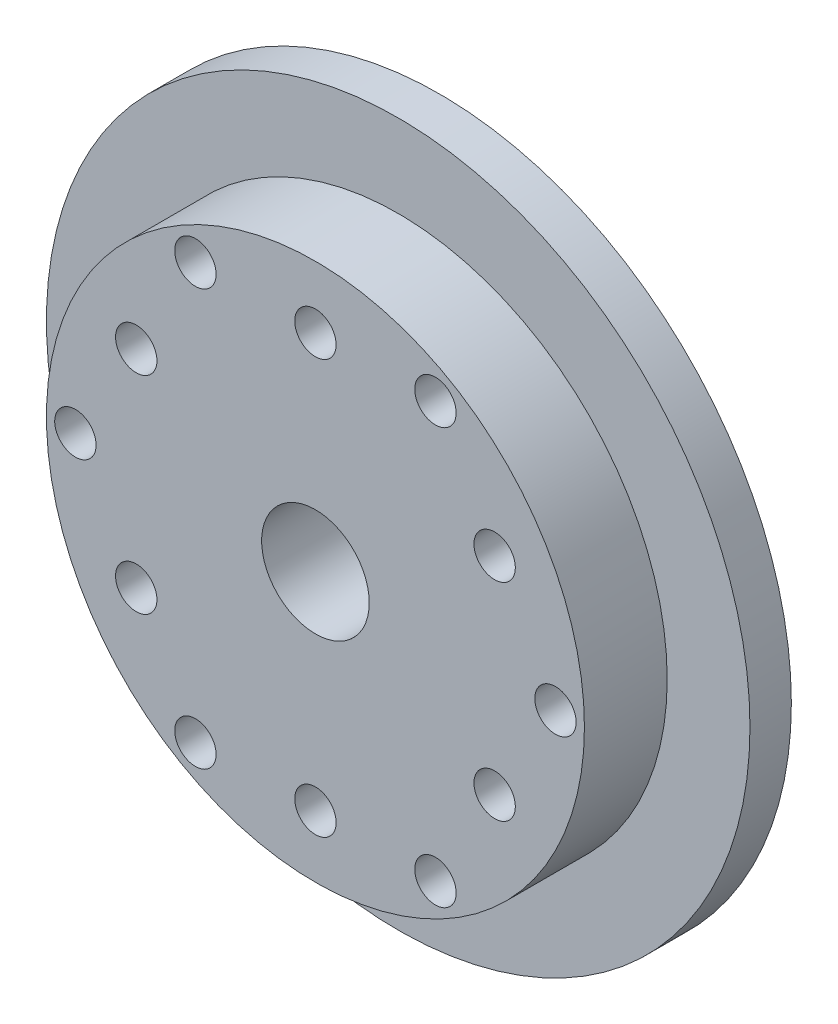
SolidWorks part; units mm, degrees
other "Markup1"
sketch "Sketch6"
ref_plane "Front Plane" through (0, 0, 0) normal (0, 0, 1) x (1, 0, 0)
ref_plane "Top Plane" through (0, 0, 0) normal (0, 1, 0) x (1, 0, 0)
ref_plane "Right Plane" through (0, 0, 0) normal (1, 0, 0) x (0, 0, -1)
sketch "Sketch1" plane through (0, 0, 0) normal (0, 0, 1) x (1, 0, 0)
  circle A0 centre (0, 0) radius 12
  circle A1 centre (0, 0) radius 42.5
  dimension "D1" = 24
  dimension "D2" = 85
extrude "Boss-Extrude1" add sketch "Sketch1" along normal blind 5
sketch "Sketch2" plane through (0, 0, 5) normal (0, 0, 1) x (1, 0, 0)
  circle A0 centre (0, 0) radius 32.5
  circle A1 centre (0, 0) radius 6.5
  dimension "D1" = 65
  dimension "D2" = 13
extrude "Boss-Extrude2" add sketch "Sketch2" along normal blind 10
sketch "Sketch3" plane through (0, 0, 0) normal (0, 0, -1) x (-1, 0, 0)
  circle A0 centre (0, 22.5) radius 4
  circle A1 centre (15.9099, 15.9099) radius 4
  circle A2 centre (22.5, 0) radius 4
  circle A3 centre (15.9099, -15.9099) radius 4
  circle A4 centre (0, -22.5) radius 4
  circle A5 centre (-15.9099, -15.9099) radius 4
  circle A6 centre (-22.5, 0) radius 4
  circle A7 centre (-15.9099, 15.9099) radius 4
  point P19 (0, 0)
  dimension "D1" = 8
  dimension "D2" = 22.5
  dimension "D3" = 8
extrude "Boss-Extrude3" add sketch "Sketch3" along normal blind 10
sketch "Sketch5" plane through (0, 0, 15) normal (0, 0, 1) x (1, 0, 0)
  circle A0 centre (0, 25) radius 2.5
  circle A1 centre (21.6506, 12.5) radius 2.5
  circle A2 centre (21.6506, -12.5) radius 2.5
  circle A3 centre (0, -25) radius 2.5
  circle A4 centre (-21.6506, -12.5) radius 2.5
  circle A5 centre (-21.6506, 12.5) radius 2.5
  point P16 (0, 0)
  dimension "D1" = 5
  dimension "D2" = 25
extrude "Cut-Extrude1" cut sketch "Sketch5" against normal blind 10
sketch "Sketch7" plane through (0, 0, 15) normal (0, 0, 1) x (1, 0, 0)
  circle A0 centre (29, 0) radius 2.5
  circle A1 centre (14.5, -25.1147) radius 2.5
  circle A2 centre (-14.5, -25.1147) radius 2.5
  circle A3 centre (-29, 0) radius 2.5
  circle A4 centre (-14.5, 25.1147) radius 2.5
  circle A5 centre (14.5, 25.1147) radius 2.5
  point P15 (0, 0)
  dimension "D1" = 5
  dimension "D2" = 29
  dimension "D3" = 6
extrude "Cut-Extrude2" cut sketch "Sketch7" against normal blind 10
